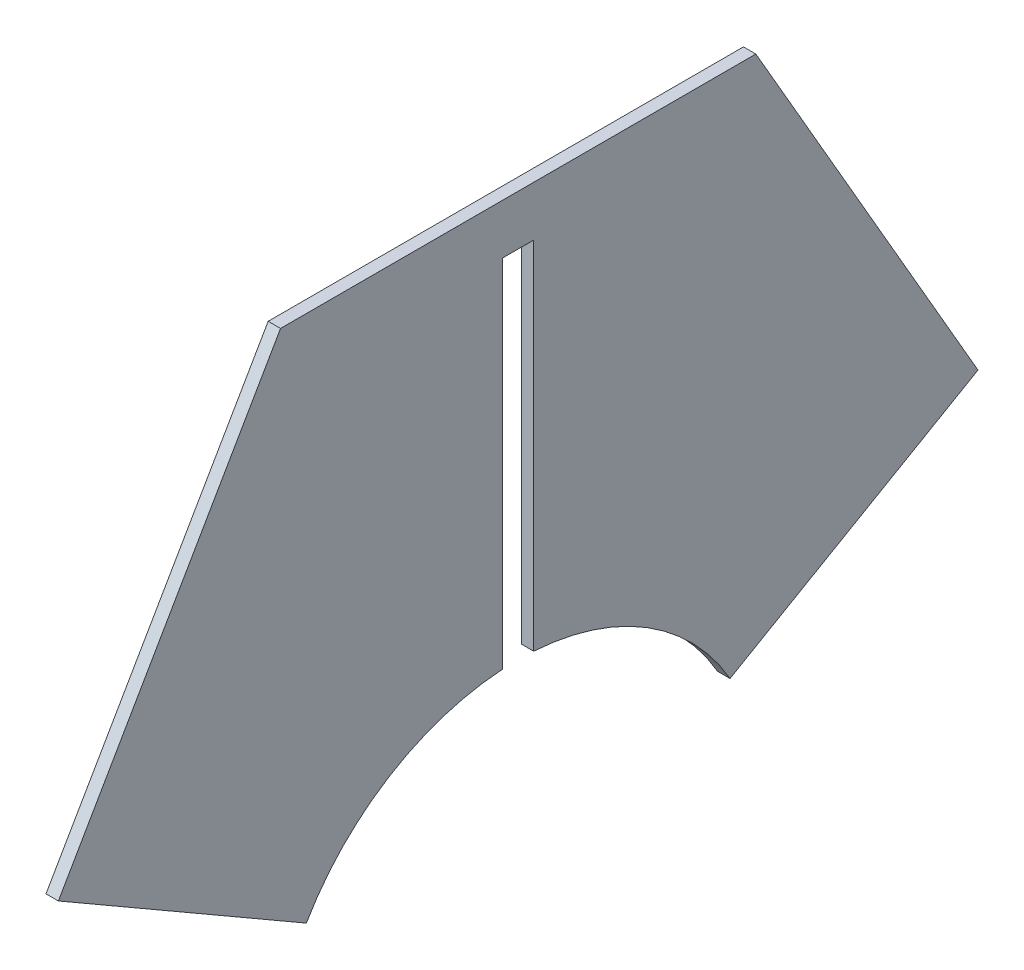
SolidWorks part; units mm, degrees
ref_plane "Plan de face" through (0, 0, 0) normal (0, 0, 1) x (1, 0, 0)
ref_plane "Plan de dessus" through (0, 0, 0) normal (0, 1, 0) x (1, 0, 0)
ref_plane "Plan de droite" through (0, 0, 0) normal (1, 0, 0) x (0, 0, -1)
sketch "Esquisse1" plane through (0, 0, 0) normal (1, 0, 0) x (0, 0, -1)
  line L0 (0, 0) -> (0, 78.8416) construction
  line L1 (0, 78.8416) -> (-5, 78.8416) construction
  line L2 (0, 78.8416) -> (5, 78.8416) construction
  line L3 (-68.416, 39.5) -> (-148.5, 85.7365)
  line L4 (-148.5, 85.7365) -> (-76.7564, 210)
  line L5 (-76.7564, 210) -> (76.7564, 210)
  line L6 (76.7564, 210) -> (148.5, 85.7365)
  line L7 (148.5, 85.7365) -> (68.416, 39.5)
  line L8 (-5, 78.8416) -> (-5, 193.8416)
  line L9 (-5, 193.8416) -> (5, 193.8416)
  line L10 (5, 193.8416) -> (5, 78.8416)
  line L11 (0, 0) -> (68.416, 39.5) construction
  line L12 (-68.416, 39.5) -> (0, 0) construction
  line L13 (0, 78.8416) -> (0, 193.8416) construction
  line L14 (0, 193.8416) -> (0, 210) construction
  line L16 (-148.5, 210) -> (148.5, 210) construction
  line L17 (-148.5, 210) -> (-148.5, 0) construction
  line L18 (-148.5, 0) -> (148.5, 0) construction
  line L19 (148.5, 210) -> (148.5, 0) construction
  arc A0 (-68.416, 39.5) -> (-5, 78.8416) centre (0, 0) cw
  arc A1 (68.416, 39.5) -> (5, 78.8416) centre (0, 0) ccw
  dimension "D5" = 79
  dimension "D1" = 60
  dimension "D2" = 60
  dimension "D3" = 297
  dimension "D4" = 210
  dimension "D6" = 10
  dimension "D7" = 115
extrude "Boss.-Extru.1" add sketch "Esquisse1" along normal blind 4
